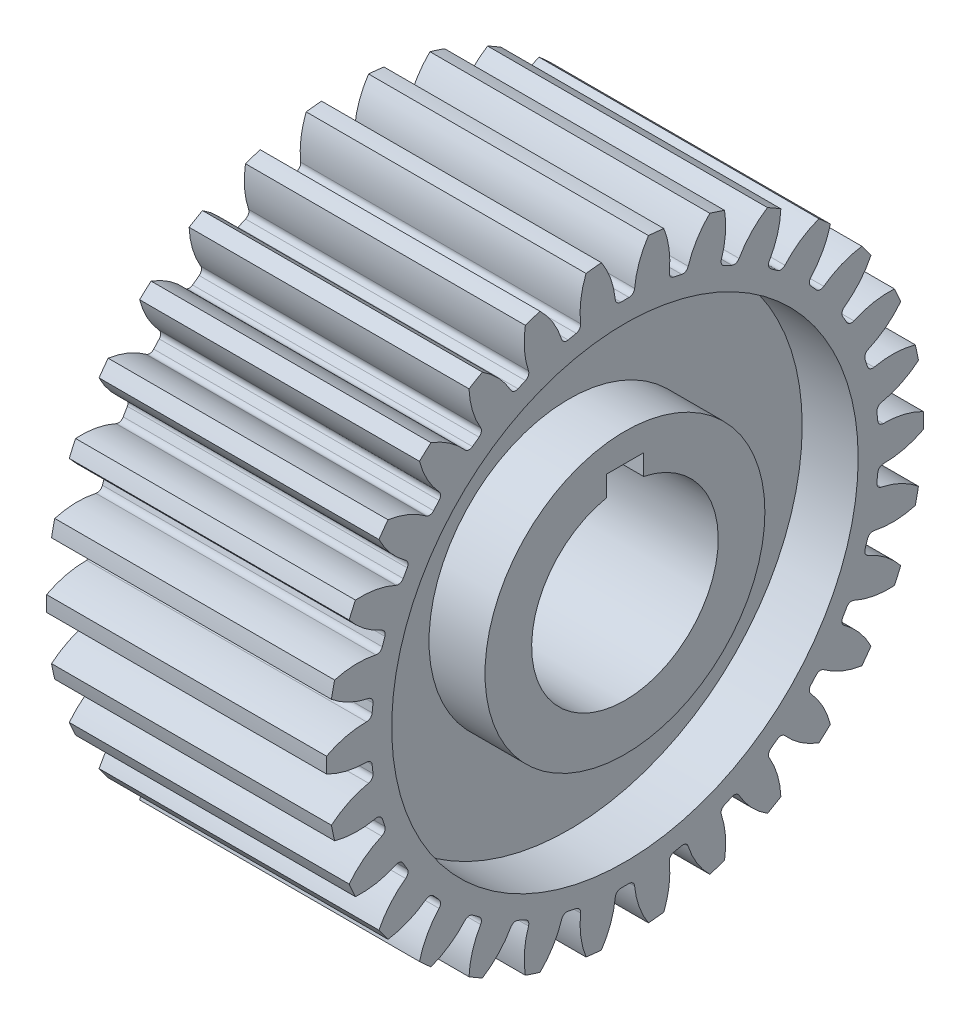
SolidWorks part; units mm, degrees
ref_plane "Front Plane" through (0, 0, 0) normal (0, 0, 1) x (1, 0, 0)
ref_plane "Top Plane" through (0, 0, 0) normal (0, 1, 0) x (1, 0, 0)
ref_plane "Right Plane" through (0, 0, 0) normal (1, 0, 0) x (0, 0, -1)
sketch "Sketch1" plane through (0, 0, 0) normal (1, 0, 0) x (0, 0, -1)
  circle A0 centre (0, 0) radius 16
  dimension "D1" = 32
extrude "Boss-Extrude1" add sketch "Sketch1" along normal mid plane 15
sketch "Sketch2" plane through (7.5, 0, 0) normal (1, 0, 0) x (0, 0, -1)
  line L3 (-1, 4.899) -> (-1, 6)
  line L4 (-1, 6) -> (1, 6)
  line L5 (1, 4.899) -> (1, 6)
  arc A0 (-1, 4.899) -> (1, 4.899) centre (0, 0) ccw
  point P4 (0, 5)
  dimension "D1" = 10
  dimension "D3" = 2
extrude "Cut-Extrude1" cut sketch "Sketch2" against normal through all
sketch "Sketch3" plane through (7.5, 0, 0) normal (1, 0, 0) x (0, 0, -1)
  circle A0 centre (0, 0) radius 12.5
  circle A1 centre (0, 0) radius 7.5
  dimension "D1" = 25
  dimension "D2" = 15
extrude "Cut-Extrude2" cut sketch "Sketch3" against normal blind 3
mirror "Mirror1" about plane through (0, 0, 0) normal (1, 0, 0) of "Cut-Extrude2"
sketch "Sketch4" plane through (7.5, 0, 0) normal (1, 0, 0) x (0, 0, -1)
  line L0 (0, 0) -> (0, 19.3885) construction
  line L1 (-0.2199, 13.6) -> (0.2199, 13.6) construction
  line L2 (-0.2199, 13.6) -> (0.2199, 13.6)
  arc A0 (0.5184, 13.8707) -> (2.08, 16.88) centre (5.0567, 13.4256) cw
  arc A2 (-0.5184, 13.8707) -> (-2.08, 16.88) centre (-5.0567, 13.4256) ccw
  arc A3 (-2.08, 16.88) -> (2.08, 16.88) centre (0, -0.9994) cw
  arc A4 (0.2199, 13.6) -> (0.5184, 13.8707) centre (0.2199, 13.9) ccw
  arc A5 (-0.5184, 13.8707) -> (-0.2199, 13.6) centre (-0.2199, 13.9) ccw
  point P8 (0, 13.6)
  point P13 (0.5, 13.6)
  point P16 (-0.5, 13.6)
  dimension "D5" = 4.56
  dimension "D6" = 18
  dimension "D7" = 0.3
  dimension "D1" = 0.5
  dimension "D2" = 13.6
  dimension "D3" = 1.58
  dimension "D4" = 3.28
extrude "Cut-Extrude3" cut sketch "Sketch4" against normal through all
pattern_circular "CirPattern2" count 30 over 360 about axis through (0, 0, 0) along (1, 0, 0) of "Cut-Extrude3"
